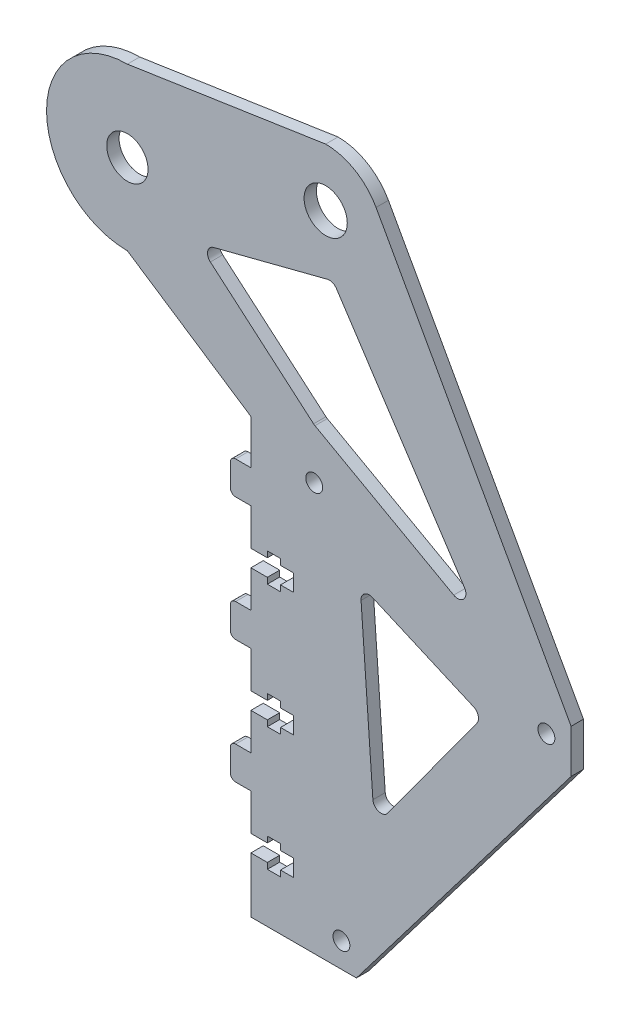
SolidWorks part; units mm, degrees
ref_plane "前视基准面" through (0, 0, 0) normal (0, 0, 1) x (1, 0, 0)
ref_plane "上视基准面" through (0, 0, 0) normal (0, 1, 0) x (1, 0, 0)
ref_plane "右视基准面" through (0, 0, 0) normal (1, 0, 0) x (0, 0, -1)
sketch "草图1" plane through (0, 0, 0) normal (0, 0, 1) x (1, 0, 0)
  line L4 (298.5456, -83.8944) -> (298.5456, -92.8418)
  line L15 (298.5456, -96.9418) -> (302.5456, -96.9418)
  line L16 (302.5456, -96.9418) -> (302.5456, -98.3918)
  line L17 (302.5456, -98.3918) -> (305.7456, -98.3918)
  line L18 (305.7456, -98.3918) -> (305.7456, -96.9418)
  line L19 (305.7456, -96.9418) -> (308.9456, -96.9418)
  line L20 (308.9456, -96.9418) -> (308.9456, -92.8418)
  line L21 (308.9456, -92.8418) -> (305.7456, -92.8418)
  line L22 (305.7456, -92.8418) -> (305.7456, -91.3918)
  line L23 (305.7456, -91.3918) -> (302.5456, -91.3918)
  line L24 (302.5456, -91.3918) -> (302.5456, -92.8418)
  line L25 (302.5456, -92.8418) -> (298.5456, -92.8418)
  line L27 (298.5456, -94.8944) -> (302.5431, -94.8944) construction
  line L28 (298.5456, -109.8944) -> (303.5456, -109.8944) construction
  line L29 (303.5456, -113.8944) -> (293.5456, -113.8944) construction
  line L30 (303.5456, -113.8944) -> (303.5456, -105.8944) construction
  line L31 (303.5456, -105.8944) -> (293.5456, -105.8944) construction
  line L32 (293.5456, -113.8944) -> (293.5456, -105.8944)
  line L33 (303.5456, -113.8944) -> (293.5456, -105.8944) construction
  line L34 (303.5456, -105.8944) -> (293.5456, -113.8944) construction
  line L35 (302.5456, -126.947) -> (298.5456, -126.947)
  line L36 (298.5456, -122.847) -> (302.5456, -122.847)
  line L37 (302.5456, -128.397) -> (302.5456, -126.947)
  line L38 (305.7456, -128.397) -> (302.5456, -128.397)
  line L39 (305.7456, -126.947) -> (305.7456, -128.397)
  line L40 (308.9456, -126.947) -> (305.7456, -126.947)
  line L41 (308.9456, -122.847) -> (308.9456, -126.947)
  line L42 (305.7456, -122.847) -> (308.9456, -122.847)
  line L43 (305.7456, -121.397) -> (305.7456, -122.847)
  line L44 (302.5456, -121.397) -> (305.7456, -121.397)
  line L45 (302.5456, -122.847) -> (302.5456, -121.397)
  line L46 (293.5456, -75.8944) -> (293.5456, -83.8944)
  line L47 (302.5456, -62.8418) -> (298.5456, -62.8418)
  line L48 (298.5456, -66.9418) -> (302.5456, -66.9418)
  line L49 (302.5456, -66.9418) -> (302.5456, -68.3918)
  line L50 (302.5456, -68.3918) -> (305.7456, -68.3918)
  line L51 (305.7456, -68.3918) -> (305.7456, -66.9418)
  line L52 (305.7456, -66.9418) -> (308.9456, -66.9418)
  line L53 (308.9456, -66.9418) -> (308.9456, -62.8418)
  line L54 (308.9456, -62.8418) -> (305.7456, -62.8418)
  line L55 (305.7456, -62.8418) -> (305.7456, -61.3918)
  line L56 (305.7456, -61.3918) -> (302.5456, -61.3918)
  line L57 (302.5456, -61.3918) -> (302.5456, -62.8418)
  line L58 (293.5456, -83.8944) -> (298.5456, -83.8944)
  line L59 (293.5456, -75.8944) -> (298.5456, -75.8944)
  line L60 (298.5456, -75.8944) -> (298.5456, -66.9418)
  line L63 (298.5456, -105.8944) -> (293.5456, -105.8944)
  line L64 (293.5456, -113.8944) -> (298.5456, -113.8944)
  line L65 (298.5456, -113.8944) -> (298.5456, -122.847)
  line L66 (308.9456, -64.8918) -> (305.2429, -64.8918) construction
  line L67 (293.5456, -45.8892) -> (298.5456, -45.8892)
  line L68 (293.5456, -53.8892) -> (293.5456, -45.8892)
  line L69 (293.5456, -53.8892) -> (298.5456, -53.8892)
  line L70 (298.5456, -53.8892) -> (298.5456, -62.8418)
  line L78 (298.5456, -126.947) -> (298.5456, -140.447)
  line L79 (298.5456, -140.447) -> (324.1889, -140.447)
  line L84 (376.3586, -71.947) -> (324.1889, -140.447)
  line L85 (298.5456, -45.8892) -> (298.5456, -35.097)
  line L89 (320.5456, -134.447) -> (313.937, -41.347) construction
  line L90 (313.937, -41.347) -> (370.3586, -65.947) construction
  line L91 (370.3586, -65.947) -> (320.5456, -134.447) construction
  line L92 (354.9473, -70.1368) -> (328.5796, -106.3961)
  line L93 (328.5796, -106.3961) -> (325.0814, -57.1152)
  line L94 (325.0814, -57.1152) -> (354.9473, -70.1368)
  line L100 (268.537, 4.3962) -> (257.1349, 16.1265) construction
  line L101 (298.5456, -96.9418) -> (298.5456, -105.8944)
  line L106 (268.537, 4.3962) -> (349.5648, 26.1075) construction
  line L112 (268.537, 4.3962) -> (268.537, -15.2492) construction
  line L116 (376.3586, -71.947) -> (376.3586, -61.3918)
  line L118 (376.3586, -61.3918) -> (328.9618, 24.0947)
  line L120 (268.537, -15.2492) -> (313.937, -41.347) construction
  line L121 (370.3586, -65.947) -> (376.3586, -61.3918) construction
  line L122 (268.537, 4.3962) -> (328.9618, 24.0947) construction
  line L123 (318.5275, 3.4237) -> (285.7813, -5.0152)
  line L124 (285.7813, -5.0152) -> (313.9369, -29.1657)
  line L125 (313.9369, -29.1657) -> (354.9472, -52.0158)
  line L128 (354.9472, -52.0158) -> (318.5275, 3.4237)
  line L129 (316.7177, 31.3062) -> (268.537, 24.0416)
  line L130 (298.5456, -35.097) -> (268.537, -15.2492)
  circle A11 centre (268.537, 4.3962) radius 5.0225
  circle A24 centre (320.5456, -134.447) radius 2.05
  circle A25 centre (370.3586, -65.947) radius 2.05
  circle A26 centre (313.937, -41.347) radius 2.05
  circle A43 centre (309.9322, -83.9678) radius 1.65 construction
  circle A50 centre (316.7177, 17.3062) radius 5.25
  circle A51 centre (316.7177, 17.3062) radius 14 construction
  circle A53 centre (268.537, 4.3962) radius 50 construction
  arc A62 (316.7177, 31.3062) -> (328.9618, 24.0947) centre (316.7177, 17.3062) cw
  circle A63 centre (268.537, 4.3962) radius 19.6454 construction
  arc A65 (268.537, -15.2492) -> (268.537, 24.0416) centre (268.537, 4.3962) cw
  point P20 (300.5444, -94.8944)
  point P30 (298.5456, -109.8944)
  dimension "D3" = 4.1
  dimension "D4" = 10.045
  dimension "D5" = 3.2
  dimension "D6" = 105
  dimension "D15" = 22
  dimension "D17" = 6
  dimension "D13" = 10.5
  dimension "D8" = 4
  dimension "D9" = 2.0526
  dimension "D10" = 15
  dimension "D11" = 8
  dimension "D12" = 10
  dimension "D14" = 13.5
  dimension "D16" = 6
  dimension "D18" = 6
  dimension "D30" = 7
  dimension "D21" = 10
extrude "凸台-拉伸1" add sketch "草图1" along normal blind 3
sketch "草图2" plane through (298.5456, 0, 0) normal (-1, 0, 0) x (0, 0, 1)
  line L0 (1.5, -66.9418) -> (1.5, -62.8418)
  line L1 (3, -66.9418) -> (0, -66.9418) construction
  line L2 (3, -62.8418) -> (0, -62.8418) construction
  circle A0 centre (1.5, -64.8918) radius 2.05
fillet "圆角1" radius 2 7 edges at (325.0814, -57.1152, 1.5) (328.5796, -106.3961, 1.5) (354.9473, -70.1368, 1.5) (313.9369, -29.1657, 1.5) (285.7813, -5.0152, 1.5) (318.5275, 3.4237, 1.5) (354.9472, -52.0158, 1.5)
fillet "圆角2" radius 1.3 6 edges at (293.5456, -45.8892, 1.5) (293.5456, -53.8892, 1.5) (293.5456, -83.8944, 1.5) (293.5456, -75.8944, 1.5) (293.5456, -113.8944, 1.5) (293.5456, -105.8944, 1.5)
